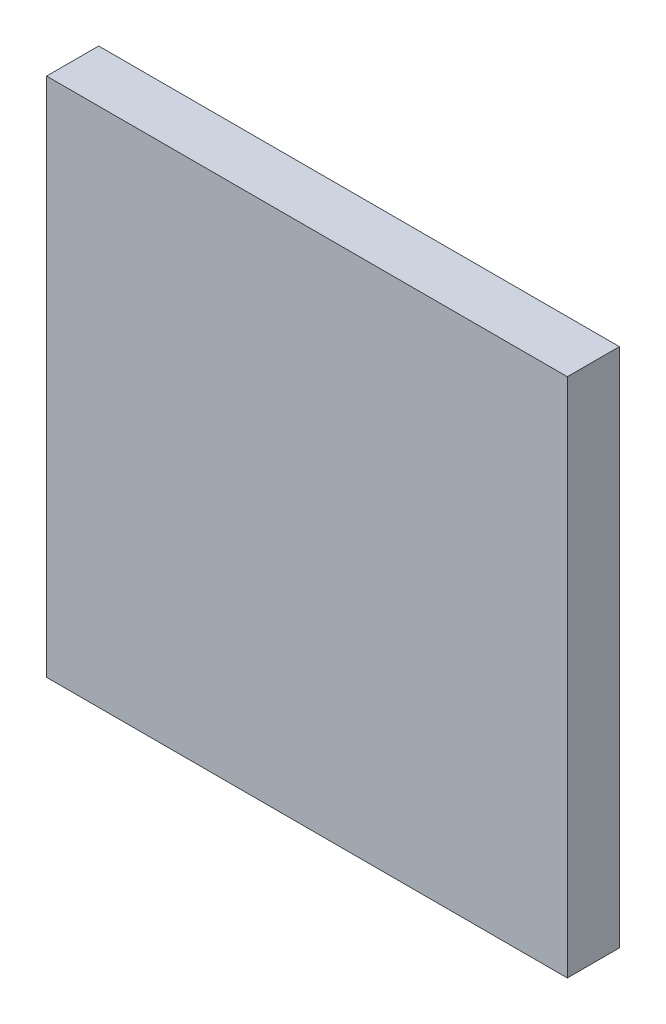
SolidWorks part; units mm, degrees
material "Лист 4,0 ГОСТ 19903-2015 / Ст3сп ГОСТ 14637-89"
ref_plane "Спереди" through (0, 0, 0) normal (0, 0, 1) x (1, 0, 0)
ref_plane "Сверху" through (0, 0, 0) normal (0, 1, 0) x (1, 0, 0)
ref_plane "Справа" through (0, 0, 0) normal (1, 0, 0) x (0, 0, -1)
sketch "Эскиз1" plane through (0, 0, 0) normal (0, 0, 1) x (1, 0, 0)
  line L1 (-20, -20) -> (20, -20)
  line L2 (-20, -20) -> (-20, 20)
  line L3 (-20, 20) -> (20, 20)
  line L4 (20, -20) -> (20, 20)
extrude "Бобышка-Вытянуть1" add sketch "Эскиз1" along normal blind 4
sketch "Эскиз2" plane through (0, 0, 0) normal (0, 0, 1) x (1, 0, 0)
  line L1 (20, -20) -> (120, -20)
  line L2 (20, -20) -> (20, 20)
  line L3 (20, 20) -> (120, 20)
  line L4 (120, -20) -> (120, 20)
extrude "Бобышка-Вытянуть2" [suppressed] add sketch "Эскиз2" along normal blind 4
